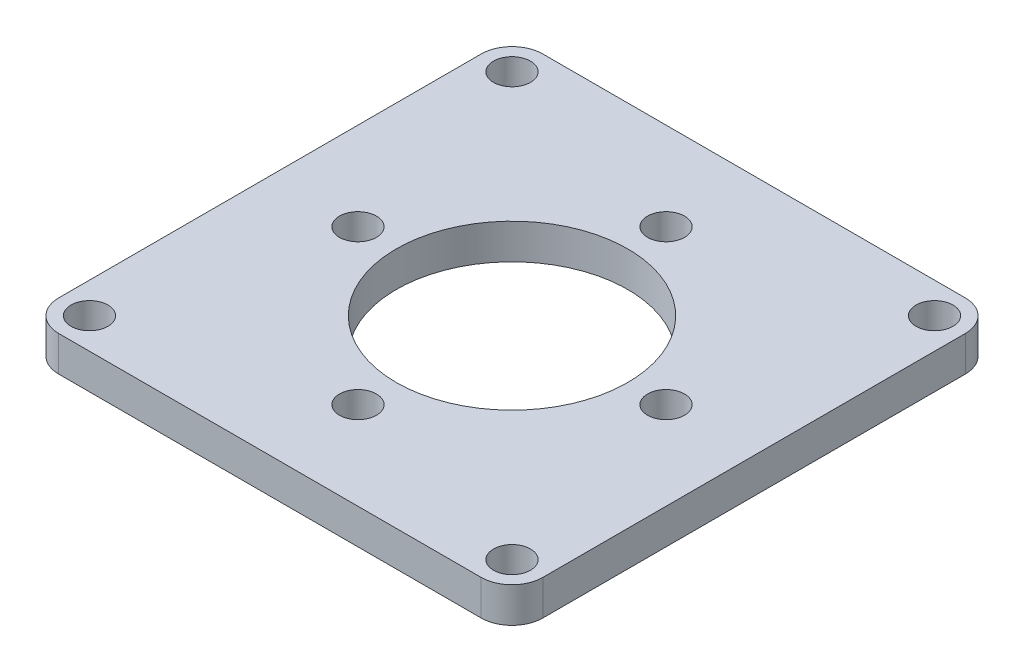
SolidWorks part; units mm, degrees
material "1060 合金"
ref_plane "前视基准面" through (0, 0, 0) normal (0, 0, 1) x (1, 0, 0)
ref_plane "上视基准面" through (0, 0, 0) normal (0, 1, 0) x (1, 0, 0)
ref_plane "右视基准面" through (0, 0, 0) normal (1, 0, 0) x (0, 0, -1)
sketch "草图1" plane through (0, 0, 0) normal (0, 1, 0) x (1, 0, 0)
  line L1 (-27.5, -27.5) -> (27.5, -27.5)
  line L2 (-27.5, -27.5) -> (-27.5, 27.5)
  line L3 (-27.5, 27.5) -> (27.5, 27.5)
  line L4 (27.5, -27.5) -> (27.5, 27.5)
  line L5 (-27.5, -27.5) -> (27.5, 27.5) construction
  line L6 (-27.5, 27.5) -> (27.5, -27.5) construction
  point P0 (0, 0)
  dimension "D1" = 55
  dimension "D2" = 55
extrude "凸台-拉伸1" add sketch "草图1" along normal blind 4
fillet "圆角1" radius 3.5 4 edges at (-27.5, 2, -27.5) (27.5, 2, -27.5) (27.5, 2, 27.5) (-27.5, 2, 27.5)
sketch "草图2" plane through (0, 4, 0) normal (0, 1, 0) x (1, 0, 0)
  circle A0 centre (0, 0) radius 13.15
  dimension "D1" = 26.3
extrude "切除-拉伸1" cut sketch "草图2" against normal blind 4
sketch "草图3" plane through (0, 4, 0) normal (0, 1, 0) x (1, 0, 0)
  line L0 (0, 0) -> (0, 17.5)
  line L1 (24, 27.5) -> (-24, 27.5) construction
  circle A0 centre (0, 0) radius 17.5
  circle A1 centre (0, 17.5) radius 2.1
  dimension "D2" = 35
  dimension "D3" = 4.2
  dimension "D1" = 90
extrude "切除-拉伸2" cut sketch "草图3" against normal blind 4 contours L0 A1 A0 | A0 A1 L0 | A0 A1
pattern_circular "阵列(圆周)1" count 4 over 360 about axis through (0, 0, 0) along (0, 1, 0) of "切除-拉伸2"
sketch "草图4" plane through (0, 4, 0) normal (0, 1, 0) x (1, 0, 0)
  line L1 (24, -24) -> (-24, -24)
  line L2 (24, -24) -> (24, 24)
  line L3 (24, 24) -> (-24, 24)
  line L4 (-24, -24) -> (-24, 24)
  line L5 (24, -24) -> (-24, 24) construction
  line L6 (24, 24) -> (-24, -24) construction
  circle A0 centre (-24, 24) radius 2.1
  point P0 (0, 0)
  dimension "D3" = 4.2
  dimension "D1" = 48
  dimension "D2" = 48
extrude "切除-拉伸3" cut sketch "草图4" against normal blind 4 contours L4 A0 L3 | L3 A0 L4
pattern_circular "阵列(圆周)2" count 4 over 360 about axis through (0, 0, 0) along (0, 1, 0) of "切除-拉伸3"
